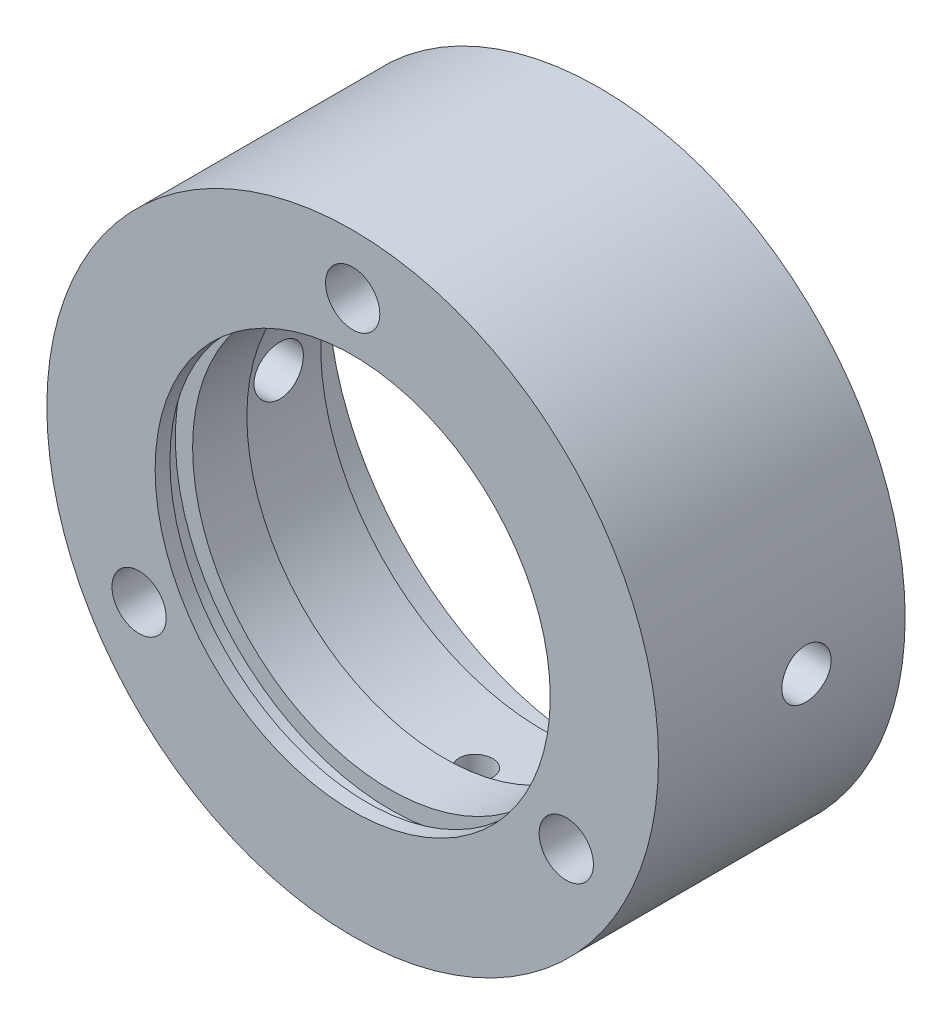
SolidWorks part; units mm, degrees
material "1.4404 (X2CrNiMo17-12-2"
ref_plane "Ebene1" through (0, 0, 0) normal (0, 0, 1) x (1, 0, 0)
ref_plane "Ebene2" through (0, 0, 0) normal (0, 1, 0) x (1, 0, 0)
ref_plane "Ebene3" through (0, 0, 0) normal (1, 0, 0) x (0, 0, -1)
sketch "Skizze1" plane through (0, 0, 0) normal (0, 0, 1) x (1, 0, 0)
  circle A0 centre (0, 0) radius 62
  point P3 (0, 11.5)
  dimension "D1" = 124
extrude "Linear austragen1" add sketch "Skizze1" along normal mid plane 50
ref_plane "Rohmaßebene" through (0, 0, -28) normal (0, 0, 1) x (1, 0, 0)
sketch "Skizze2" plane through (0, 0, 0) normal (1, 0, 0) x (0, 0, -1)
  line L0 (0, 0) -> (32.0891, 0) construction
  line L1 (25, 55.05) -> (13.5, 55.05)
  line L2 (25, -62) -> (25, 62) construction
  line L3 (13.5, 55.05) -> (13.5, 45)
  line L4 (-6.4, 40.05) -> (-17.4, 40.05)
  line L5 (13.5, 45) -> (-6.4, 45)
  line L6 (-6.4, 45) -> (-6.4, 40.05)
  line L7 (-25, 62) -> (-25, -62) construction
  line L8 (25, 55.05) -> (25, 0)
  line L9 (-25, 40.05) -> (-25, 0)
  line L10 (25, 0) -> (-25, 0)
  line L11 (-22, 40.05) -> (-25, 40.05)
  line L13 (-22, 40.05) -> (-22, 43.55)
  line L14 (-22, 43.55) -> (-17.4, 43.55)
  line L15 (-17.4, 40.05) -> (-17.4, 43.55)
  dimension "D1" = 110.1
  dimension "D2" = 80.1
  dimension "D3" = 11.5
  dimension "D4" = 90
  dimension "D5" = 19.9
  dimension "D6" = 4.6
  dimension "D7" = 3.5
  dimension "D8" = 3
revolve "Schnitt-Rotation1" cut sketch "Skizze2" angle 360 about L0
hole_wizard "Stirnsenkung für M6 Zylinderschraube mit Innensechskant1" positions "Skizze4" profile "Skizze3" counterbore size "M6" standard "DIN" end condition through all
sketch "Skizze4" plane through (-59.1911, 8.6807, 25) normal (0, 0, 1) x (1, 0, 0)
  circle A0 centre (59.1911, -8.6807) radius 50 construction
  point P0 (59.1911, 41.3193)
  point P12 (102.4924, -33.6807)
  point P13 (15.8898, -33.6807)
  dimension "D1" = 100
sketch "Skizze3" plane through (0, 50, 25) normal (1, 0, 0) x (0, -1, 0)
  line L0 (0, 0) -> (0, 50)
  line L1 (0, 50) -> (3.3, 50)
  line L3 (3.3, 50) -> (3.3, 9.4)
  line L4 (3.3, 9.4) -> (5.5, 9.4)
  line L5 (5.5, 9.4) -> (5.5, 0)
  line L7 (5.5, 0) -> (0, 0)
  line L11 (0, -6.35) -> (0, 107.95) construction
  dimension "Bohrerdurchmesser" = 6.6
  dimension "Bohrungstiefe" = 50
  dimension "Senkdurchmesser2" = 11
  dimension "Senktiefe2" = 9.4
hole_wizard "M8 Gewindebohrung1" [suppressed] positions "Skizze6" profile "Skizze5" tap size "M8" standard "DIN"
sketch "Skizze6" plane through (0, 0, 20.4) normal (0, 0, 1) x (1, 0, 0)
  line L0 (0, 0) -> (51.9615, 30) construction
  line L1 (0, 0) -> (0, 41.0965) construction
  circle A0 centre (0, 0) radius 60 construction
  point P0 (51.9615, 30)
  point P18 (0, -60)
  point P19 (-51.9615, 30)
  dimension "D1" = 60
sketch "Skizze5" plane through (51.9615, 30, 20.4) normal (1, 0, 0) x (0, -1, 0)
  line L0 (0, 0) -> (0, 42.9)
  line L1 (0, 42.9) -> (3.4, 42.9)
  line L2 (3.4, 42.9) -> (3.4, 0)
  line L5 (3.4, 0) -> (0, 0)
  line L11 (0, -6.35) -> (0, 107.95) construction
  dimension "Bohrerdurchmesser" = 6.8
  dimension "Bohrungstiefe" = 42.9
cosmetic thread "Bohrungsgewinde1" [suppressed] parameters "D2"=8
cosmetic thread "Bohrungsgewinde2" [suppressed] parameters "D2"=8
cosmetic thread "Bohrungsgewinde3" [suppressed] parameters "D2"=8
ref_plane "Ebene4" through (-62, 0, 0) normal (-1, 0, 0) x (0, 1, 0)
hole_wizard "Ø12.0 (12) Durchmesser Bohrung1" positions "Skizze8" profile "Skizze7" hole size "Ø12.0" standard "DIN"
sketch "Skizze8" plane through (-62, 0, 0) normal (-1, 0, 0) x (0, 1, 0)
  line L0 (-62, -25) -> (62, -25) construction
  point P0 (0, 5)
  dimension "D1" = 30
sketch "Skizze7" plane through (-62, 0, -5) normal (0, 1, 0) x (0, 0, 1)
  line L0 (0, 0) -> (0, 124)
  line L1 (0, 124) -> (5, 124)
  line L2 (5, 124) -> (5, 0)
  line L5 (5, 0) -> (0, 0)
  line L11 (0, -6.35) -> (0, 107.95) construction
  dimension "Bohrerdurchmesser" = 10
  dimension "Bohrungstiefe" = 124
mirror "Spiegeln1" about plane through (0, 0, 0) normal (1, 0, 0) of "Ø12.0 (12) Durchmesser Bohrung1"
ref_plane "Ebene5" through (0, -62, 0) normal (0, 1, 0) x (1, 0, 0)
sketch "Skizze10" plane through (0, -62, 0) normal (0, 1, 0) x (1, 0, 0)
  circle A0 centre (0, 0) radius 5
  dimension "D1" = 10
extrude "Schnitt-Linear austragen3" cut sketch "Skizze10" along normal blind 0.1
hole_wizard "M8 Gewindebohrung3" positions "Skizze12" profile "Skizze11" tap size "M8" standard "Gabler-Normteile"
sketch "Skizze12" plane through (0, -61.9, 0) normal (0, -1, 0) x (-1, 0, 0)
  point P0 (0, 0)
cosmetic thread "Bohrungsgewinde5" parameters "D2"=8
sketch "Skizze11" plane through (0, -61.9, 0) normal (1, 0, 0) x (0, 0, -1)
  line L0 (0, 0) -> (0, 16.9)
  line L1 (0, 16.9) -> (3.4, 16.9)
  line L2 (3.4, 16.9) -> (3.4, 0)
  line L5 (3.4, 0) -> (0, 0)
  line L11 (0, -6.35) -> (0, 107.95) construction
  dimension "Bohrerdurchmesser" = 6.8
  dimension "Bohrungstiefe" = 16.9
equation "\"D1@Rohmaßebene\" = \"D1@Linear austragen1\" + 3"
